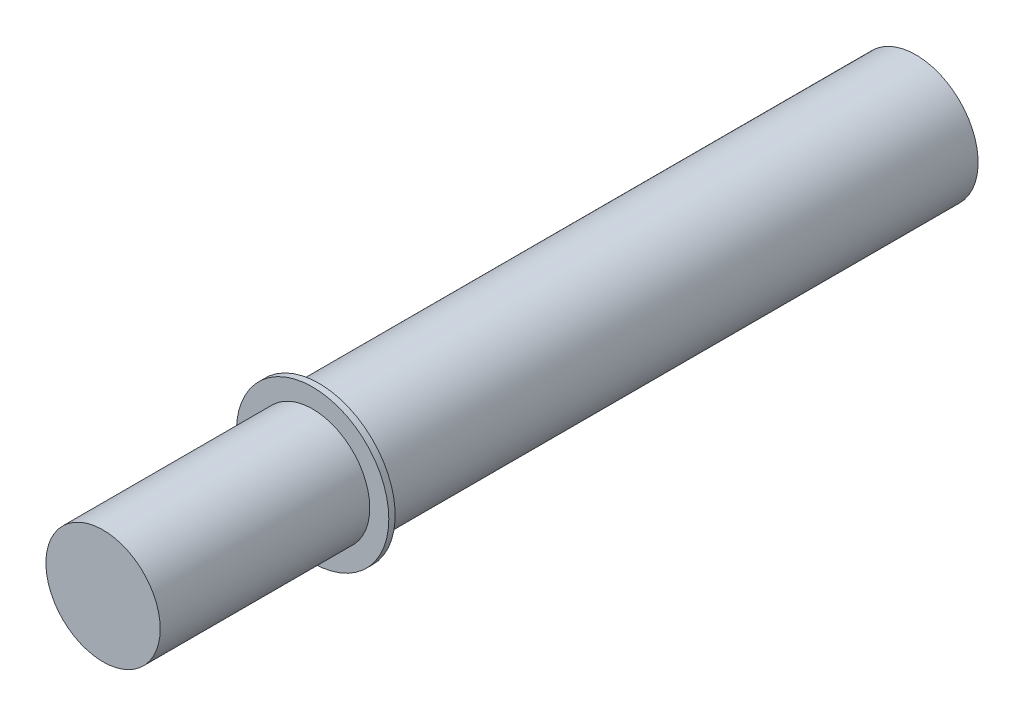
SolidWorks part; units mm, degrees
ref_plane "Płaszczyzna przednia" through (0, 0, 0) normal (0, 0, 1) x (1, 0, 0)
ref_plane "Płaszczyzna górna" through (0, 0, 0) normal (0, 1, 0) x (1, 0, 0)
ref_plane "Płaszczyzna prawa" through (0, 0, 0) normal (1, 0, 0) x (0, 0, -1)
sketch "Szkic1" plane through (0, 0, 0) normal (0, 0, 1) x (1, 0, 0)
  circle A0 centre (0, 0) radius 6
  dimension "D1" = 12
extrude "Dodanie-wyciągnięcie1" add sketch "Szkic1" along normal blind 64
sketch "Szkic2" plane through (0, 0, 0) normal (0, 0, -1) x (-1, 0, 0)
  circle A0 centre (0, 0) radius 4.9
  dimension "D1" = 9.8
extrude "Wytnij-wyciągnięcie1" cut sketch "Szkic2" against normal blind 47 flip side to cut
sketch "Szkic3" plane through (0, 0, 64) normal (0, 0, 1) x (1, 0, 0)
  circle A0 centre (0, 0) radius 4.5
  dimension "D1" = 9
extrude "Wytnij-wyciągnięcie2" cut sketch "Szkic3" against normal blind 16.5 flip side to cut
